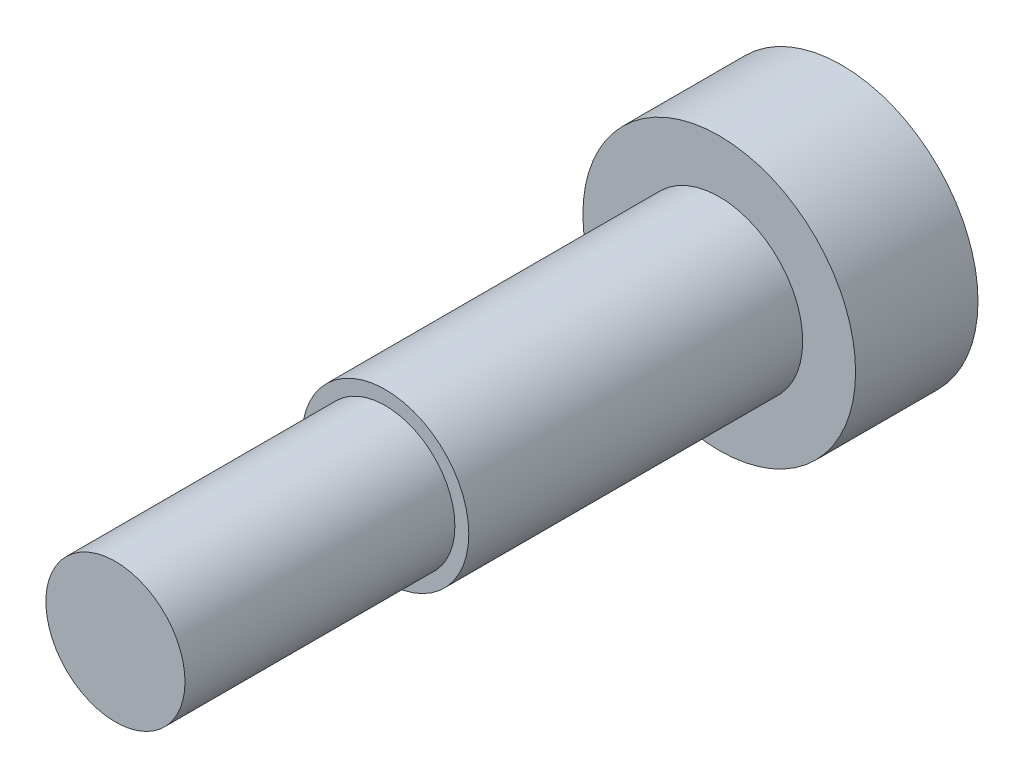
SolidWorks part; units mm, degrees
ref_plane "前视基准面" through (0, 0, 0) normal (0, 0, 1) x (1, 0, 0)
ref_plane "上视基准面" through (0, 0, 0) normal (0, 1, 0) x (1, 0, 0)
ref_plane "右视基准面" through (0, 0, 0) normal (1, 0, 0) x (0, 0, -1)
sketch "草图1" plane through (0, 0, 0) normal (0, 0, 1) x (1, 0, 0)
  circle A0 centre (0, 0) radius 4.9
  dimension "D1" = 9.8
extrude "凸台-拉伸1" add sketch "草图1" along normal blind 4.4
sketch "草图2" plane through (0, 0, 4.4) normal (0, 0, 1) x (1, 0, 0)
  circle A0 centre (0, 0) radius 3
  dimension "D1" = 6
extrude "凸台-拉伸2" add sketch "草图2" along normal blind 12
sketch "草图3" plane through (0, 0, 16.4) normal (0, 0, 1) x (1, 0, 0)
  circle A0 centre (0, 0) radius 2.5
  dimension "D1" = 5
extrude "凸台-拉伸3" add sketch "草图3" along normal blind 9.7
sketch "草图4" plane through (0, 0, 0) normal (0, 0, -1) x (-1, 0, 0)
  line L1 (0, 1.7321) -> (-1.5, 0.866)
  line L2 (-1.5, 0.866) -> (-1.5, -0.866)
  line L3 (-1.5, -0.866) -> (0, -1.7321)
  line L4 (0, -1.7321) -> (1.5, -0.866)
  line L5 (1.5, -0.866) -> (1.5, 0.866)
  line L6 (1.5, 0.866) -> (0, 1.7321)
  circle A0 centre (0, 0) radius 1.5 construction
  dimension "D1" = 3
extrude "切除-拉伸1" cut sketch "草图4" against normal blind 2
